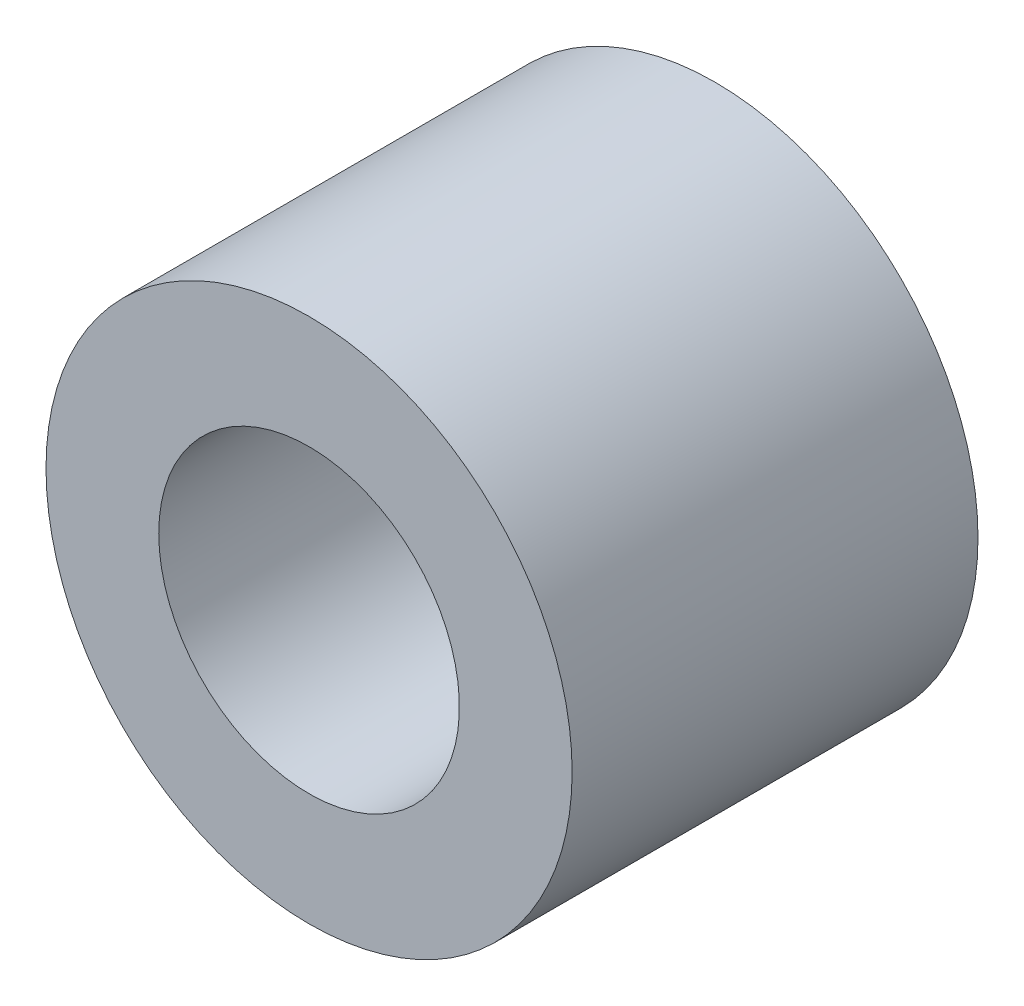
SolidWorks part; units mm, degrees
ref_plane "Front" through (0, 0, 0) normal (0, 0, 1) x (1, 0, 0)
ref_plane "Top" through (0, 0, 0) normal (0, 1, 0) x (1, 0, 0)
ref_plane "Right" through (0, 0, 0) normal (1, 0, 0) x (0, 0, -1)
sketch "草图1" plane through (0, 0, 0) normal (0, 0, 1) x (1, 0, 0)
  circle A0 centre (0, 0) radius 2
  circle A1 centre (0, 0) radius 3.5
  dimension "D1" = 7
  dimension "D2" = 4
extrude "凸台-拉伸1" add sketch "草图1" along normal blind 5.4
